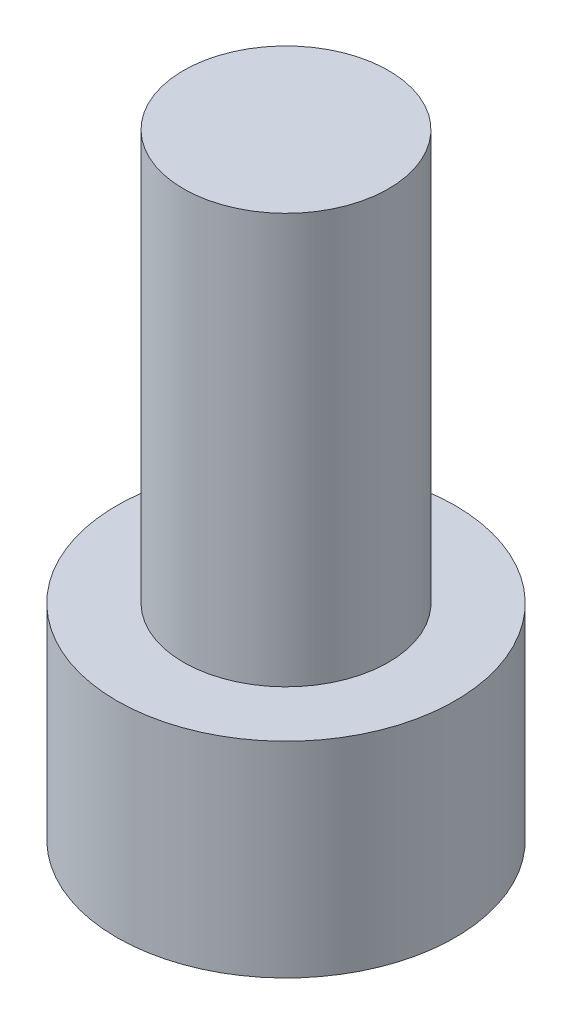
SolidWorks part; units mm, degrees
ref_plane "前视基准面" through (0, 0, 0) normal (0, 0, 1) x (1, 0, 0)
ref_plane "上视基准面" through (0, 0, 0) normal (0, 1, 0) x (1, 0, 0)
ref_plane "右视基准面" through (0, 0, 0) normal (1, 0, 0) x (0, 0, -1)
other "Configuration Table"
sketch "草图1" plane through (0, 0, 0) normal (0, 1, 0) x (1, 0, 0)
  circle A0 centre (0, 0) radius 6.6
  dimension "D1" = 13.2
extrude "凸台-拉伸1" add sketch "草图1" along normal blind 8
sketch "草图2" plane through (0, 8, 0) normal (0, 1, 0) x (1, 0, 0)
  circle A0 centre (0, 0) radius 4
  dimension "D1" = 8
extrude "凸台-拉伸2" add sketch "草图2" along normal blind 16
cosmetic thread "装饰螺纹线1" parameters "D1"=16, "D2"=7
sketch "草图3" plane through (0, 0, 0) normal (0, -1, 0) x (1, 0, 0)
  line L1 (2.8052, -2.0324) -> (3.1627, 1.4132)
  line L2 (3.1627, 1.4132) -> (0.3575, 3.4456)
  line L3 (0.3575, 3.4456) -> (-2.8052, 2.0324)
  line L4 (-2.8052, 2.0324) -> (-3.1627, -1.4132)
  line L5 (-3.1627, -1.4132) -> (-0.3575, -3.4456)
  line L6 (-0.3575, -3.4456) -> (2.8052, -2.0324)
  circle A1 centre (0, 0) radius 3 construction
  dimension "D1" = 6
extrude "切除-拉伸1" cut sketch "草图3" against normal blind 4
